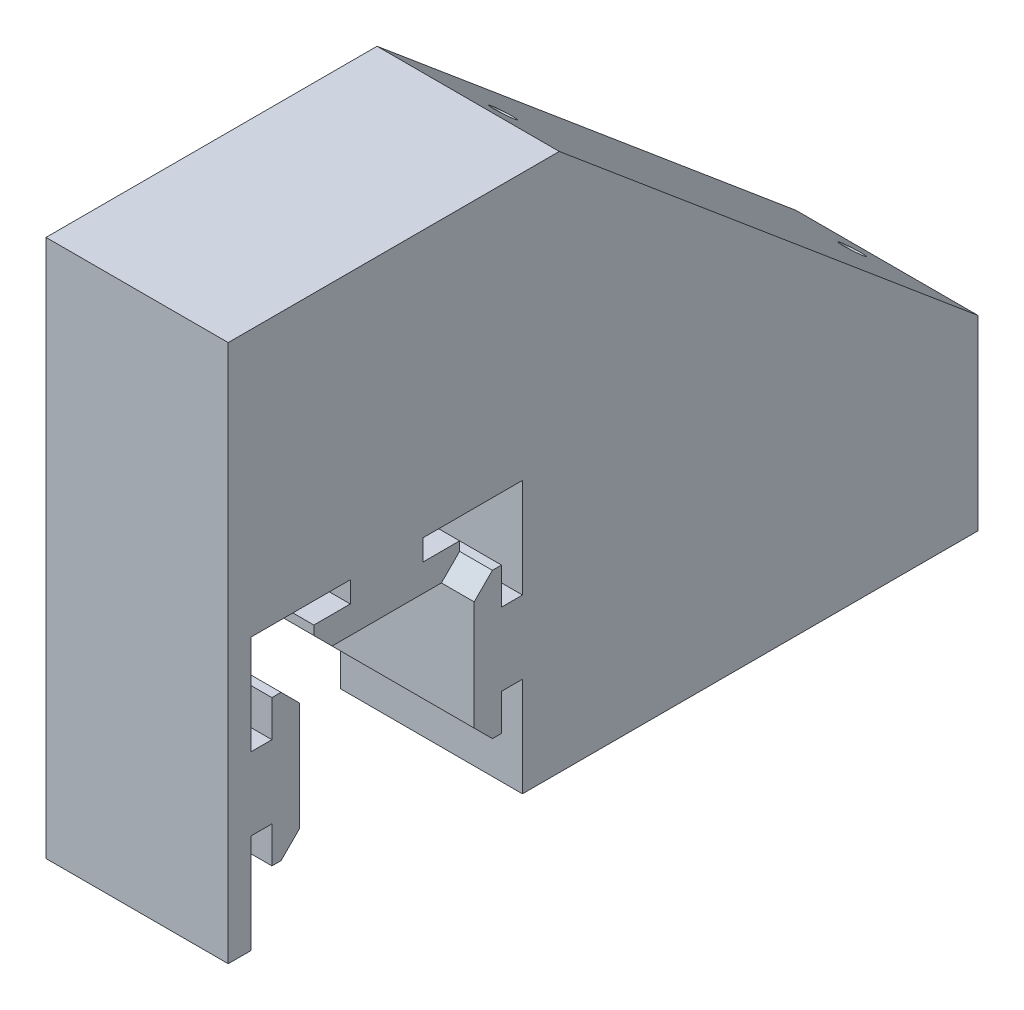
SolidWorks part; units mm, degrees
material "PF"
ref_plane "Plan de face" through (0, 0, 0) normal (0, 0, 1) x (1, 0, 0)
ref_plane "Plan de dessus" through (0, 0, 0) normal (0, 1, 0) x (1, 0, 0)
ref_plane "Plan de droite" through (0, 0, 0) normal (1, 0, 0) x (0, 0, -1)
sketch "Esquisse1" plane through (0, 0, 0) normal (1, 0, 0) x (0, 0, -1)
  line L3 (4.8, 18.9) -> (2.5, 18.9)
  line L9 (4.8, 10.9) -> (2.5, 10.9)
  line L13 (7.8, 8.9) -> (7.8, 20.9)
  line L17 (2.5, 18.9) -> (2.5, 29.8)
  line L18 (2.5, 29.8) -> (13.4, 29.8)
  line L19 (13.4, 29.8) -> (13.4, 27.5)
  line L22 (11.4, 24.5) -> (23.4, 24.5)
  line L25 (21.4, 27.5) -> (21.4, 29.8)
  line L26 (21.4, 29.8) -> (32.3, 29.8)
  line L27 (32.3, 29.8) -> (32.3, 18.9)
  line L28 (32.3, 18.9) -> (30, 18.9)
  line L31 (27, 20.9) -> (27, 8.9)
  line L34 (30, 10.9) -> (32.3, 10.9)
  line L35 (32.3, 10.9) -> (32.3, 0)
  line L36 (2.5, 10.9) -> (2.5, 0)
  line L37 (2.5, 0) -> (0, 0)
  line L40 (0, 59.0475) -> (36.3373, 59.0475)
  line L42 (0, 59.0475) -> (0, 0)
  line L44 (82.3, 20.4802) -> (36.3373, 59.0475)
  line L45 (82.3, 20.4802) -> (82.3, 0)
  line L47 (32.3, 0) -> (82.3, 0)
  line L50 (4.8, 18.9) -> (4.8, 22.9)
  line L51 (4.8, 22.9) -> (5.8, 22.9)
  line L52 (13.4, 27.5) -> (9.4, 27.5)
  line L53 (9.4, 27.5) -> (9.4, 26.5)
  line L54 (9.4, 26.5) -> (11.4, 24.5)
  line L55 (21.4, 27.5) -> (25.4, 27.5)
  line L56 (25.4, 27.5) -> (25.4, 26.5)
  line L57 (25.4, 26.5) -> (23.4, 24.5)
  line L58 (30, 18.9) -> (30, 22.9)
  line L59 (30, 22.9) -> (29, 22.9)
  line L60 (29, 22.9) -> (27, 20.9)
  line L61 (27, 8.9) -> (29, 6.9)
  line L62 (29, 6.9) -> (30, 6.9)
  line L63 (30, 6.9) -> (30, 10.9)
  line L64 (4.8, 6.9) -> (5.8, 6.9)
  line L65 (5.8, 6.9) -> (7.8, 8.9)
  line L66 (4.8, 10.9) -> (4.8, 6.9)
  line L67 (5.8, 22.9) -> (7.8, 20.9)
  dimension "D2" = 60
  dimension "D3" = 135
  dimension "D4" = 2.3
  dimension "D5" = 25
  dimension "D6" = 16
  dimension "D7" = 1
  dimension "D8" = 8
  dimension "D9" = 10.9
  dimension "D10" = 3
  dimension "D11" = 3
  dimension "D12" = 8
  dimension "D13" = 40
  dimension "D14" = 2.5
  dimension "D15" = 50
  dimension "D16" = 3
extrude "Boss.-Extru.1" add sketch "Esquisse1" along normal blind 20 contours L35 L47 L45 L44 L40 L42 L37 L36 L9 L66 L64 L65 L13 L67 L51 L50 L3 L17 L18 L19 L52 L53 L54 L22 L57 L56 L55 L25 L26 L27 L28 L58 L59 L60 L31 L61 L62 L63 L34
hole_wizard "Trou pour taraudage pour trou taraudé M3x0.51" positions "Esquisse2" profile "Esquisse3" hole size "M3x0.5" standard "Ansi Metric"
sketch "Esquisse2" plane through (0, 52.5431, -44.0889) normal (0, 0.766, -0.6428) x (1, 0, 0)
  line L0 (20, -10.119) -> (0, -10.119) construction
  line L1 (10, -5.119) -> (10, -10.119) construction
  line L4 (20, 49.881) -> (0, 49.881) construction
  line L5 (10, 49.881) -> (10, 44.881) construction
  point P0 (10, -5.119)
  point P2 (10, 44.881)
  point P9 (10, -10.119)
  dimension "D1" = 50
sketch "Esquisse3" plane through (10, 55.8335, -40.1676) normal (1, 0, 0) x (0, 0.6428, 0.766)
  line L0 (0, 0) -> (0, 6.7511)
  line L1 (0, 6.7511) -> (1.25, 6)
  line L2 (1.25, 6) -> (1.25, 0)
  line L5 (1.25, 0) -> (0, 0)
  line L10 (0, 6.7511) -> (-1.25, 6) construction
  line L11 (0, -6.35) -> (0, 107.95) construction
  dimension "Diamètre du perçage" = 2.5
  dimension "Profondeur du perçage" = 6
  dimension "Angle de pointe" = 118
